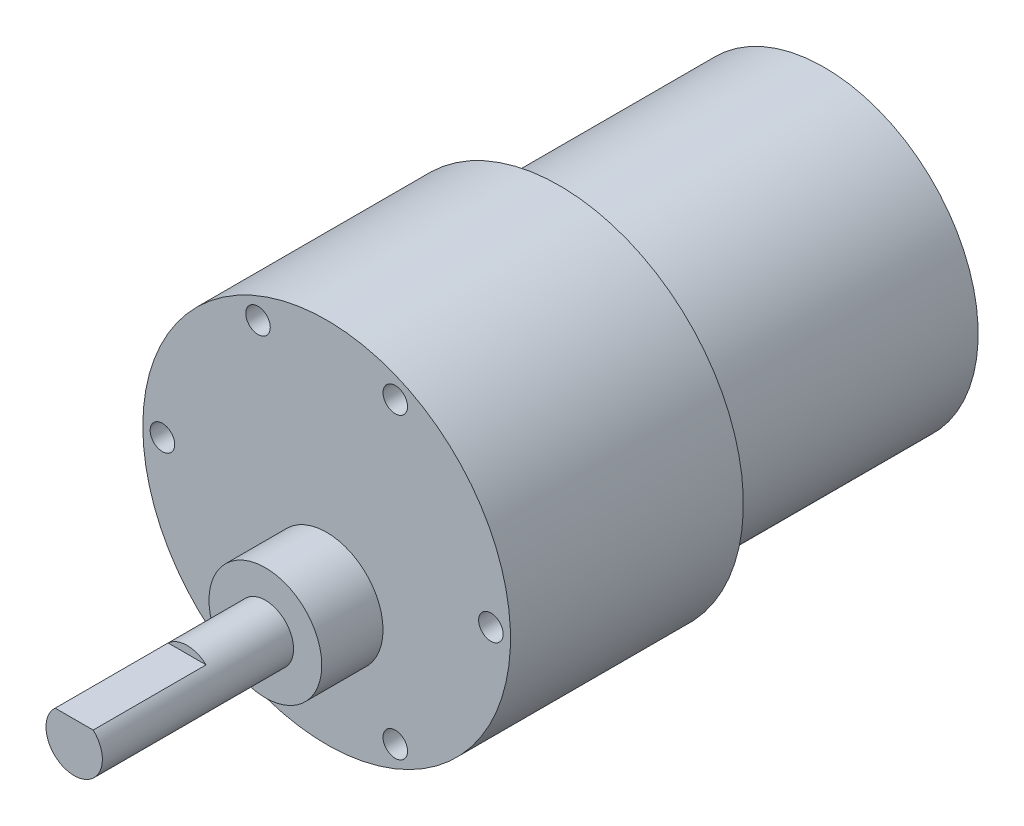
SolidWorks part; units mm, degrees
ref_plane "Front Plane" through (0, 0, 0) normal (0, 0, 1) x (1, 0, 0)
ref_plane "Top Plane" through (0, 0, 0) normal (0, 1, 0) x (1, 0, 0)
ref_plane "Right Plane" through (0, 0, 0) normal (1, 0, 0) x (0, 0, -1)
sketch "Sketch1" plane through (0, 0, 0) normal (0, 0, 1) x (1, 0, 0)
  circle A0 centre (0, 0) radius 19.05
  dimension "D1" = 38.1
extrude "Boss-Extrude1" add sketch "Sketch1" along normal blind 24.13
sketch "Sketch2" plane through (0, 0, 0) normal (0, 0, -1) x (-1, 0, 0)
  circle A0 centre (0, 0) radius 15.95
  dimension "D1" = 31.9
extrude "Boss-Extrude2" add sketch "Sketch2" along normal blind 27.432 separate body
sketch "Sketch3" plane through (0, 0, 24.13) normal (0, 0, 1) x (1, 0, 0)
  line L0 (0, 19.05) -> (0, -19.05) construction
  circle A0 centre (0, -5.842) radius 5.842
  circle A2 centre (0, 0) radius 19.05 construction
  point P2 (0, 0)
  dimension "D1" = 11.684
extrude "Boss-Extrude3" add sketch "Sketch3" along normal blind 6.35
sketch "Sketch4" plane through (0, 0, 30.48) normal (0, 0, 1) x (1, 0, 0)
  circle A0 centre (0, -5.842) radius 2.921
  dimension "D1" = 5.842
extrude "Boss-Extrude4" add sketch "Sketch4" along normal blind 19.812
sketch "Sketch5" plane through (0, 0, 50.292) normal (0, 0, 1) x (1, 0, 0)
  line L1 (-1.9675, -3.683) -> (1.9675, -3.683)
  line L2 (-1.9675, -3.683) -> (-1.9675, -2.921)
  line L3 (-1.9675, -2.921) -> (1.9675, -2.921)
  line L4 (1.9675, -3.683) -> (1.9675, -2.921)
  circle A0 centre (0, -5.842) radius 2.921 construction
  dimension "D1" = 0.762
extrude "Cut-Extrude1" cut sketch "Sketch5" against normal blind 11.7
sketch "Sketch6" plane through (0, 0, 24.13) normal (0, 0, 1) x (1, 0, 0)
  line L0 (-5.842, -5.842) -> (-5.842, -17.3298) construction
  line L1 (-5.842, -5.842) -> (-5.842, 17.3298) construction
  line L2 (-7.112, 15.4607) -> (-17.018, 0) construction
  line L3 (-17.018, 0) -> (-7.112, -15.4607) construction
  line L4 (0, 18.288) -> (0, -18.288) construction
  line L5 (5.842, -5.842) -> (5.842, 17.3298) construction
  line L6 (5.842, -5.842) -> (5.842, -17.3298) construction
  line L7 (-17.018, 0) -> (17.018, 0) construction
  circle A0 centre (-7.112, 15.4607) radius 1.27
  circle A1 centre (-7.112, -15.4607) radius 1.27
  circle A2 centre (-17.018, 0) radius 1.27
  circle A3 centre (0, 0) radius 18.288 construction
  circle A4 centre (0, -5.842) radius 5.842 construction
  circle A5 centre (0, -5.842) radius 5.842 construction
  circle A6 centre (7.112, 15.4607) radius 1.27
  circle A7 centre (7.112, -15.4607) radius 1.27
  circle A8 centre (17.018, 0) radius 1.27
  dimension "D1" = 2.54
  dimension "D2" = 36.576
extrude "Cut-Extrude2" cut sketch "Sketch6" against normal blind 3.302
equation "\"FoamCore\" = \".2\""
equation "\"MDF\" = \".2\""
equation "\"GMaterial\"= \".2\""
equation "\"PVCMountDiameter\" = \"0.5in\""
equation "\"PVCMountDistanceToEdge\" = \"0.5\""
equation "\"PVCThickness\" = \"0.13in\""
equation "\"BaseWidth\" = \"8in\""
equation "\"BaseLength\" = \"10in\""
equation "\"BallDiameter\" = \"38mm\""
equation "\"BaseGap\" = \"4in\""
equation "\"FunnelTopDiameter\" = \"8in\""
equation "\"FunnelTopDepth\" = \"0.5in\""
equation "\"BallGap\" = \"0.1in\""
equation "\"FunnelLength\" = 3in"
equation "\"FunnelMaterial\" = 0.1in"
equation "\"FunnelLowerDiameter\" = 1.9in"
equation "\"FunnelDepth\" = 1.5in"
equation "\"AmmoFeederLength\" = 1.5in + 76mm"
equation "\"AmmoFeederCutoffLength\"= \"MovingWheelDiameter\""
equation "\"WheelThickness\" = 0.5in"
equation "\"LauncherWheelDiameter\" = 76mm"
equation "\"MotorFrontLength\" = 0.95in"
equation "\"MotorBodyTotalLength\" = 2.03in"
equation "\"MotorFrontDiameter\" = 1.5in"
equation "\"MotorLowerDriveshaftDiameter\" = 0.46in"
equation "\"MotorLowerDriveshaftThickness\" = 0.25in"
equation "\"MotorFullDriveshaftLength\" = 0.78in"
equation "\"MotorDriveshaftDiameter\" = 0.23in"
equation "\"MotorDriveshaftFlatThickness\" = 0.2in"
equation "\"MotorRearDiameter\" = 31.9mm"
equation "\"MotorDriveshaftBottomToTop\" = 31.1mm"
equation "\"MotorFlatDriveshaftLength\" = 11.7mm"
equation "\"MotorDistanceBetweenLowerandTopHoles\" = 0.5in"
equation "\"MotorMountsDistanceFromEdge\" = 0.06in"
equation "\"MotorScrewMountDiameter\" = 0.1in"
equation "\"MotorScrewMountDepth\" = 0.13in"
equation "\"HBRidgeScrewHoleDeep\" = 0.18in"
equation "\"D1@Boss-Extrude1\"=\"MotorFrontLength\""
equation "\"D1@Sketch1\"=\"MotorFrontDiameter\""
equation "\"D1@Sketch2\"=\"MotorRearDiameter\""
equation "\"D1@Boss-Extrude2\"=\"MotorBodyTotalLength\"-\"MotorFrontLength\""
equation "\"D1@Sketch3\"=\"MotorLowerDriveshaftDiameter\""
equation "\"D1@Boss-Extrude3\"=\"MotorLowerDriveshaftThickness\""
equation "\"D1@Sketch4\"=\"MotorDriveshaftDiameter\""
equation "\"D1@Boss-Extrude4\"=\"MotorFullDriveshaftLength\""
equation "\"D1@Sketch5\"=\"MotorDriveshaftDiameter\"-\"MotorDriveshaftFlatThickness\""
equation "\"D1@Cut-Extrude1\"=\"MotorFlatDriveshaftLength\""
equation "\"D1@Sketch6\"=\"MotorScrewMountDiameter\""
equation "\"D2@Sketch6\"=\"MotorFrontDiameter\"-\"MotorMountsDistanceFromEdge\""
equation "\"D1@Cut-Extrude2\"=\"MotorScrewMountDepth\""
